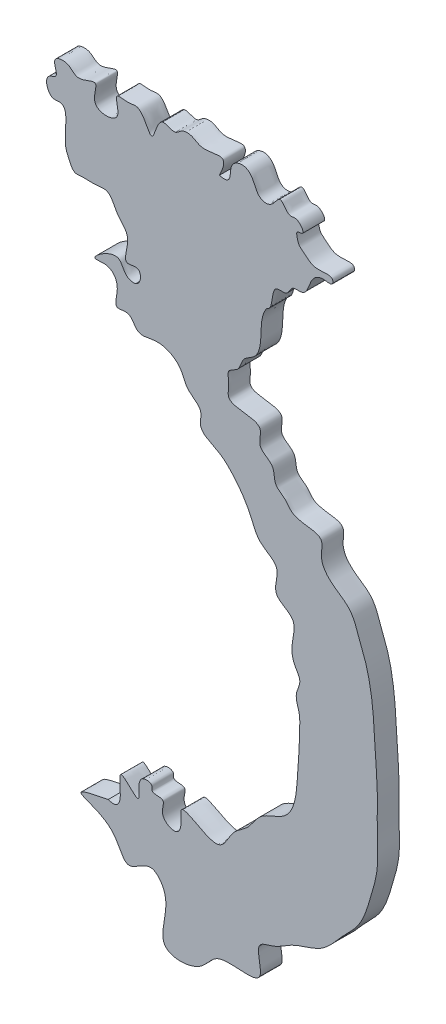
SolidWorks part; units mm, degrees
ref_plane "Front Plane" through (0, 0, 0) normal (0, 0, 1) x (1, 0, 0)
ref_plane "Top Plane" through (0, 0, 0) normal (0, 1, 0) x (1, 0, 0)
ref_plane "Right Plane" through (0, 0, 0) normal (1, 0, 0) x (0, 0, -1)
sketch "Sketch1" plane through (0, 0, 0) normal (0, 0, 1) x (1, 0, 0)
  spline S0 degree 3 poles (-14.1182, 11.5795) (-12.0646, 11.0481) (-13.3737, 13.6787) (-10.8211, 14.6884) (-9.2653, 13.5107) (-8.9844, 11.5057) (-6.7206, 11.3138) (-5.6939, 13.8547) (-4.6916, 11.2785) (-3.2756, 11.9867) (-2.0102, 10.1434) (-3.6012, 10.3516) (-3.3332, 9.3982) (-3.1642, 8.6825) (-2.3292, 8.0605) (-1.3503, 7.1617) (0.0079, 7.091) (1.5846, 7.2974) (1.5901, 5.9917) (-0.2991, 6.6935) (-1.4214, 5.4629) (-1.8069, 4.1752) (-2.512, 2.9517) (-4.1964, 3.511) (-4.6192, 1.6971) (-7.3077, 2.5604) (-6.5295, -0.8738) (-7.5698, -1.0939) knots 0 0 0 0 0.088043 0.136072 0.169062 0.236156 0.272754 0.322275 0.371796 0.39467 0.436702 0.455564 0.478438 0.492905 0.518784 0.558138 0.59685 0.637231 0.64638 0.685976 0.739603 0.764239 0.799969 0.836853 0.872583 0.909466 1 1 1 1
  spline S1 degree 3 poles (-7.5698, -1.0939) (-8.4758, -2.3789) (-8.1613, -4.6328) (-8.8232, -7.8262) (-11.0657, -8.5725) (-11.2149, -10.5685) (-13.2277, -11.0608) (-12.6295, -12.7885) (-13.5758, -15.7463) (-7.4594, -14.5404) (-9.1021, -18.4487) (-6.3104, -19.2494) (-6.7161, -21.7849) (-4.9298, -22.5497) (-3.7355, -24.8098) (0.7065, -23.907) (-0.3763, -27.5676) (1.4036, -29.7728) (4.299, -31.2163) (5.1168, -34.1765) (6.2018, -36.7491) (6.9031, -39.7419) (7.2714, -43.3698) (7.4635, -47.3844) (7.8316, -51.7078) (7.619, -56.1053) (7.9764, -60.5935) (6.7397, -64.6573) (5.5897, -68.5711) (2.629, -71.2128) (0.2326, -74.5105) (-3.897, -75.1918) (-6.2092, -77.1216) (-9.1984, -77.6149) (-8.4832, -79.8876) (-8.3, -83.2649) (-14.4612, -80.8789) (-16.504, -85.4451) (-22.9094, -85.6586) (-21.3808, -80.6245) (-21.5409, -77.7067) (-23.8544, -75.2365) (-27.1436, -78.8693) (-28.858, -71.579) (-37.1288, -72.392) (-29.5007, -70.9025) knots 0 0 0 0 0.031364 0.050359 0.062605 0.076421 0.086696 0.097089 0.109214 0.142828 0.156686 0.173833 0.18816 0.201164 0.210371 0.241733 0.25559 0.275807 0.298149 0.322949 0.337749 0.359174 0.388824 0.416592 0.44609 0.482465 0.511911 0.542162 0.574007 0.59731 0.626873 0.658851 0.68086 0.694052 0.713106 0.720035 0.762558 0.786243 0.820886 0.850203 0.872986 0.886515 0.91048 0.936517 1 1 1 1
  spline S2 degree 3 poles (-29.5007, -70.9025) (-26.6952, -71.9596) (-29.5453, -63.9752) (-24.3295, -70.7449) (-25.9698, -65.5888) (-23.2637, -65.931) (-23.652, -67.245) (-21.2716, -66.7472) (-22.7055, -69.2347) (-19.9196, -70.7301) (-19.2677, -68.7123) (-20, -65.3163) (-13.9583, -70.7919) (-12.603, -65.994) (-9.96, -64.7951) (-8.5484, -61.7449) (-4.6804, -61.2368) (-3.4336, -57.7354) (-3.3416, -54.8589) (-3.0837, -52.0957) (-3.0276, -49.586) (-2.9279, -47.3013) (-3.857, -45.3414) (-2.5635, -43.4515) (-4.0664, -41.6718) (-4.194, -39.3406) (-3.1997, -36.1652) (-7.2778, -35.041) (-5.25, -31.1141) (-8.7935, -29.8825) (-9.9147, -26.3121) (-11.9394, -23.551) (-14.3917, -21.3163) (-17.2416, -20.4639) (-16.2353, -17.5048) (-18.7567, -16.5243) (-19.3255, -13.9412) (-21.4841, -12.6511) (-23.5602, -12.6973) (-25.6647, -13.3025) (-26.3225, -10.8333) (-28.9762, -11.8276) (-27.7413, -8.7313) (-29.1553, -6.6414) (-32.7351, -7.4563) (-27.7492, -3.89) (-27.3934, -7.1987) (-24.9653, -7.4217) (-24.9126, -4.7247) (-27.8921, -5.9894) (-26.0147, -1.9124) (-28.4166, -0.4476) (-29.2082, 2.2661) (-31.4492, 1.7608) (-32.7904, 1.9909) (-34.3343, 1.6996) (-34.9131, 3.0714) (-35.9557, 5.203) (-34.5594, 9.8137) (-37.7249, 8.9635) (-38.5876, 11.7689) (-36.0825, 11.9777) (-37.679, 14.3764) (-34.8931, 14.7465) (-33.815, 12.7845) (-30.2972, 15.1542) (-32.5023, 10.6282) (-26.9886, 10.6552) (-29.0914, 14.4967) (-26.7246, 13.812) (-24.7746, 14.5961) (-23.3296, 9.4971) (-22.6305, 15.0784) (-20.3443, 13.2204) (-19.3583, 14.471) (-17.9226, 14.5375) (-15.8643, 12.7384) (-12.3001, 15.2623) (-14.1182, 11.5795) knots 0 0 0 0 0.025553 0.04192 0.057568 0.0651 0.067562 0.076058 0.084827 0.098159 0.106008 0.114777 0.144884 0.163444 0.177538 0.193083 0.215847 0.233854 0.249674 0.265389 0.280535 0.292252 0.303855 0.314472 0.32461 0.338166 0.354429 0.370849 0.388467 0.404888 0.42042 0.450118 0.460829 0.478567 0.488053 0.503042 0.51373 0.531091 0.539222 0.550064 0.561563 0.569694 0.581891 0.597234 0.605019 0.624569 0.637063 0.645194 0.65468 0.662812 0.679074 0.694685 0.708322 0.717338 0.728017 0.73294 0.741207 0.74829 0.777173 0.782096 0.795615 0.802086 0.812527 0.822648 0.831898 0.846008 0.859567 0.876661 0.890219 0.898351 0.906482 0.923842 0.939652 0.949887 0.955624 0.963067 0.971435 1 1 1 1
extrude "Boss-Extrude3" add sketch "Sketch1" along normal blind 3
